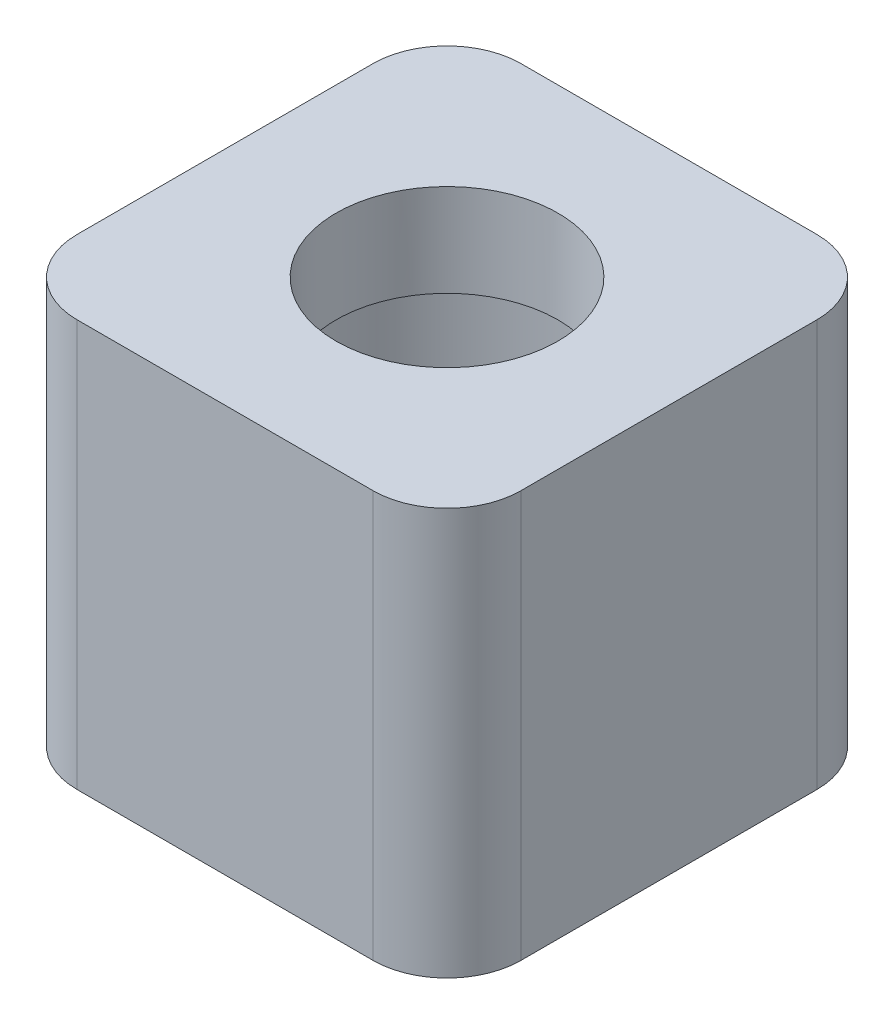
SolidWorks part; units mm, degrees
ref_plane "Front" through (0, 0, 0) normal (0, 0, 1) x (1, 0, 0)
ref_plane "Top" through (0, 0, 0) normal (0, 1, 0) x (1, 0, 0)
ref_plane "Right" through (0, 0, 0) normal (1, 0, 0) x (0, 0, -1)
sketch "Sketch1" plane through (0, 0, 0) normal (0, 1, 0) x (1, 0, 0)
  line L1 (-3.1249, 3.3134) -> (0.8751, 3.3134)
  line L2 (-4.1249, 2.3134) -> (-4.1249, -1.6866)
  line L3 (-3.1249, -2.6866) -> (0.8751, -2.6866)
  line L4 (1.8751, 2.3134) -> (1.8751, -1.6866)
  arc A0 (0.8751, 3.3134) -> (1.8751, 2.3134) centre (0.8751, 2.3134) cw
  arc A1 (0.8751, -2.6866) -> (1.8751, -1.6866) centre (0.8751, -1.6866) ccw
  arc A2 (-4.1249, -1.6866) -> (-3.1249, -2.6866) centre (-3.1249, -1.6866) ccw
  arc A3 (-3.1249, 3.3134) -> (-4.1249, 2.3134) centre (-3.1249, 2.3134) ccw
  point P6 (1.8751, 3.3134)
  point P11 (-4.1249, -2.6866)
  point P14 (-4.1249, 3.3134)
  dimension "D3" = 1
  dimension "D1" = 6
  dimension "D2" = 6
extrude "Boss-Extrude1" add sketch "Sketch1" along normal blind 5.5
sketch "Sketch2" plane through (0, 5.5, 0) normal (0, 1, 0) x (1, 0, 0)
  line L0 (-1.1249, 3.3134) -> (-1.1249, -2.6866) construction
  line L1 (0.8751, 3.3134) -> (-3.1249, 3.3134) construction
  line L2 (-3.1249, -2.6866) -> (0.8751, -2.6866) construction
  line L3 (-4.1249, 0.3134) -> (1.8751, 0.3134) construction
  line L4 (-4.1249, 2.3134) -> (-4.1249, -1.6866) construction
  line L5 (1.8751, -1.6866) -> (1.8751, 2.3134) construction
  circle A0 centre (-1.1249, 0.3134) radius 1.5
  dimension "D1" = 3
extrude "Cut-Extrude1" cut sketch "Sketch2" against normal up to surface (5.5 mm away) up to face at (-1.1249, 0, -0.3134)
sketch "Sketch3" plane through (0, 0, 0) normal (0, -1, 0) x (1, 0, 0)
  circle A0 centre (-1.1249, -0.3134) radius 2.25
  dimension "D1" = 4.5
extrude "Cut-Extrude2" cut sketch "Sketch3" against normal blind 4.25
